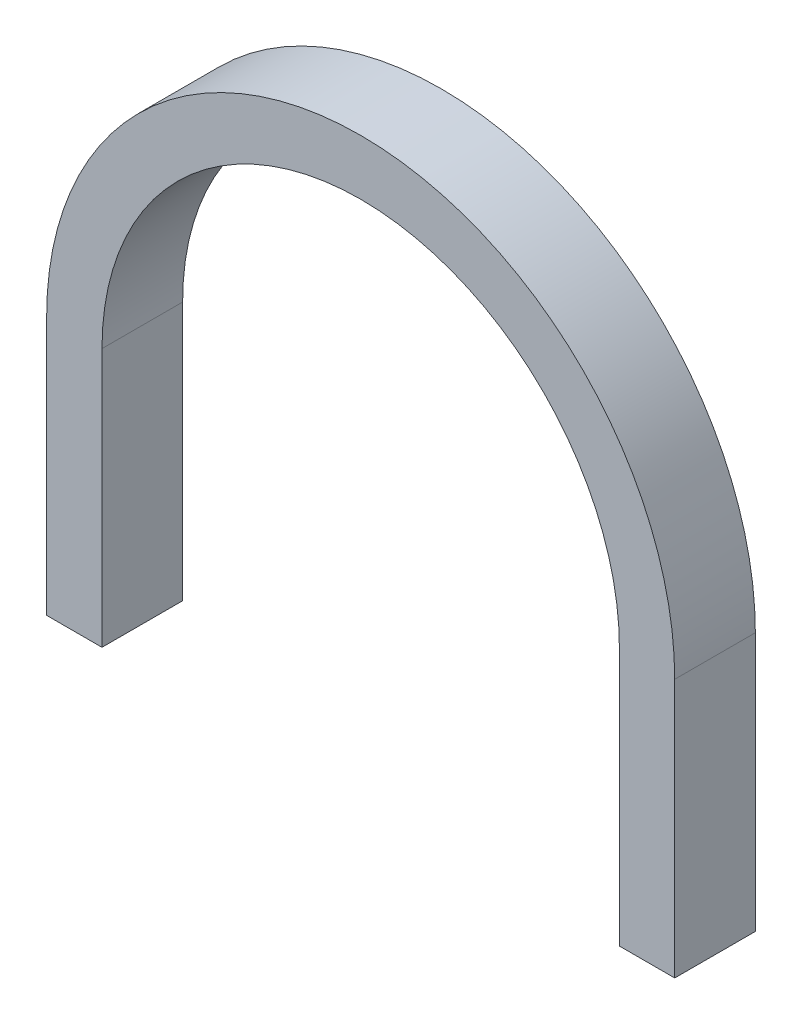
SolidWorks part; units mm, degrees
ref_plane "Front Plane" through (0, 0, 0) normal (0, 0, 1) x (1, 0, 0)
ref_plane "Top Plane" through (0, 0, 0) normal (0, 1, 0) x (1, 0, 0)
ref_plane "Right Plane" through (0, 0, 0) normal (1, 0, 0) x (0, 0, -1)
sketch "Sketch1" plane through (0, 0, 0) normal (0, 0, 1) x (1, 0, 0)
  line L0 (-12.192, -12.192) -> (-14.8, -12.192)
  line L1 (-14.8, -12.192) -> (-14.8, 0)
  line L3 (14.8, 0) -> (14.8, -12.192)
  line L4 (14.8, -12.192) -> (12.192, -12.192)
  line L5 (12.192, -12.192) -> (12.192, 0)
  line L6 (-12.192, 0) -> (-12.192, -12.192)
  circle A0 centre (0, 0) radius 12.192 construction
  arc A1 (12.192, 0) -> (-12.192, 0) centre (0, 0) ccw
  arc A2 (-14.8, 0) -> (14.8, 0) centre (0, 0) cw
  point P7 (0, 0)
  dimension "D1" = 24.384
  dimension "D2" = 29.6
extrude "Boss-Extrude1" add sketch "Sketch1" along normal blind 3.8
